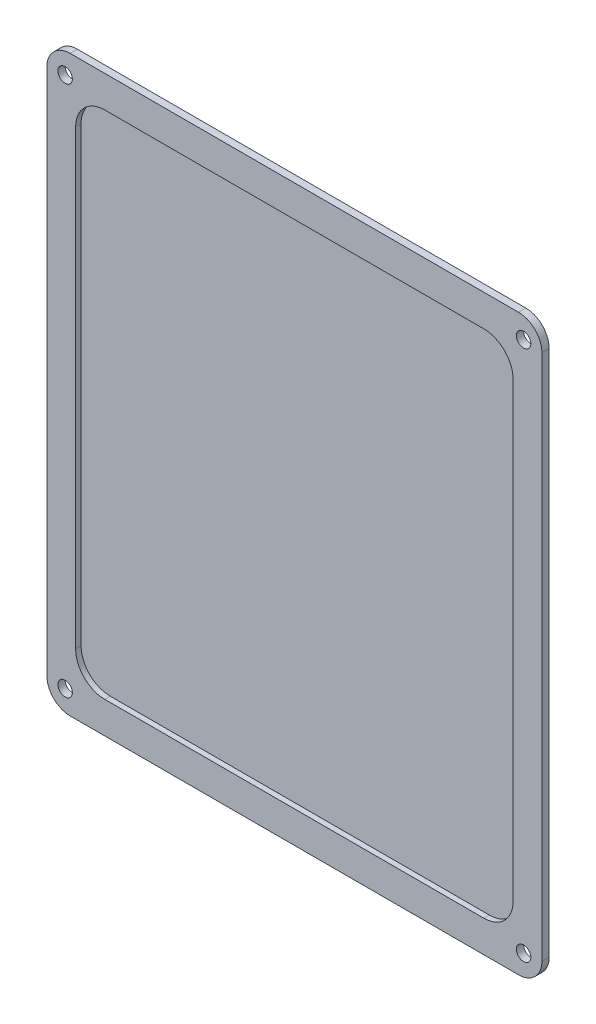
SolidWorks part; units mm, degrees
material "ABS"
ref_plane "Front Plane" through (0, 0, 0) normal (0, 0, 1) x (1, 0, 0)
ref_plane "Top Plane" through (0, 0, 0) normal (0, 1, 0) x (1, 0, 0)
ref_plane "Right Plane" through (0, 0, 0) normal (1, 0, 0) x (0, 0, -1)
sketch "Sketch1" plane through (0, 0, 0) normal (0, 0, 1) x (1, 0, 0)
  line L0 (-49.911, 57.8485) -> (-53.8932, 62.464) construction
  line L1 (-49.911, -57.8485) -> (49.911, -57.8485) construction
  line L2 (-49.911, -57.8485) -> (-49.911, 57.8485) construction
  line L3 (-49.911, 57.8485) -> (49.911, 57.8485) construction
  line L4 (49.911, -57.8485) -> (49.911, 57.8485) construction
  line L5 (-49.911, -57.8485) -> (49.911, 57.8485) construction
  line L6 (-49.911, 57.8485) -> (49.911, -57.8485) construction
  line L8 (53.8932, -62.464) -> (-53.8932, -62.464)
  line L9 (53.8932, -62.464) -> (53.8932, 62.464)
  line L10 (53.8932, 62.464) -> (-53.8932, 62.464)
  line L11 (-53.8932, -62.464) -> (-53.8932, 62.464)
  line L12 (53.8932, -62.464) -> (-53.8932, 62.464) construction
  line L13 (53.8932, 62.464) -> (-53.8932, -62.464) construction
  circle A0 centre (-49.911, 57.8485) radius 1.5748
  circle A1 centre (49.911, 57.8485) radius 1.5748
  circle A2 centre (49.911, -57.8485) radius 1.5748
  circle A3 centre (-49.911, -57.8485) radius 1.5748
  point P0 (0, 0)
  point P10 (0, 0)
  dimension "D3" = 3.1496
  dimension "D1" = 115.697
  dimension "D2" = 99.822
  dimension "D4" = 6.096
extrude "Boss-Extrude1" add sketch "Sketch1" along normal blind 1.5875
fillet "Fillet1" radius 5.08 4 edges at (-53.8932, -62.464, 0.7937) (53.8932, -62.464, 0.7937) (53.8932, 62.464, 0.7937) (-53.8932, 62.464, 0.7937)
sketch "Sketch4" plane through (0, 0, 1.5875) normal (0, 0, 1) x (1, 0, 0)
  line L1 (41.275, 55.5625) -> (-41.275, 55.5625)
  line L2 (47.625, 49.2125) -> (47.625, -49.2125)
  line L3 (41.275, -55.5625) -> (-41.275, -55.5625)
  line L4 (-47.625, 49.2125) -> (-47.625, -49.2125)
  line L5 (47.625, 55.5625) -> (-47.625, -55.5625) construction
  line L6 (47.625, -55.5625) -> (-47.625, 55.5625) construction
  arc A0 (47.625, 49.2125) -> (41.275, 55.5625) centre (41.275, 49.2125) ccw
  arc A1 (-41.275, 55.5625) -> (-47.625, 49.2125) centre (-41.275, 49.2125) ccw
  arc A2 (-47.625, -49.2125) -> (-41.275, -55.5625) centre (-41.275, -49.2125) ccw
  arc A3 (41.275, -55.5625) -> (47.625, -49.2125) centre (41.275, -49.2125) ccw
  point P0 (0, 0)
  dimension "D3" = 6.35
  dimension "D1" = 95.25
  dimension "D2" = 111.125
extrude "Cut-Extrude1" cut sketch "Sketch4" against normal through all
sketch "Sketch6" plane through (0, 0, 0) normal (0, 0, -1) x (-1, 0, 0)
  line L0 (-41.275, 55.5625) -> (41.275, 55.5625) construction
  line L1 (-47.625, -55.5625) -> (47.625, -55.5625)
  line L2 (-47.625, -55.5625) -> (-47.625, 55.5625)
  line L3 (-47.625, 55.5625) -> (47.625, 55.5625)
  line L4 (47.625, -55.5625) -> (47.625, 55.5625)
  line L5 (-47.625, -55.5625) -> (47.625, 55.5625) construction
  line L6 (-47.625, 55.5625) -> (47.625, -55.5625) construction
  line L7 (-47.625, -49.2125) -> (-47.625, 49.2125) construction
  point P0 (0, 0)
extrude "Boss-Extrude2" add sketch "Sketch6" against normal blind 0.3969
sketch "Sketch7" plane through (0, 0, 0) normal (0, 0, -1) x (-1, 0, 0)
  line L0 (-41.275, 55.5625) -> (41.275, 55.5625) construction
  line L1 (41.275, -55.5625) -> (-41.275, -55.5625)
  line L2 (47.625, -49.2125) -> (47.625, 49.2125)
  line L3 (41.275, 55.5625) -> (-41.275, 55.5625)
  line L4 (-47.625, -49.2125) -> (-47.625, 49.2125)
  line L5 (47.625, -55.5625) -> (-47.625, 55.5625) construction
  line L6 (47.625, 55.5625) -> (-47.625, -55.5625) construction
  line L7 (-47.625, -49.2125) -> (-47.625, 49.2125) construction
  arc A0 (-41.275, 55.5625) -> (-47.625, 49.2125) centre (-41.275, 49.2125) ccw
  arc A1 (-41.275, -55.5625) -> (-47.625, -49.2125) centre (-41.275, -49.2125) cw
  arc A2 (41.275, -55.5625) -> (47.625, -49.2125) centre (41.275, -49.2125) ccw
  arc A3 (47.625, 49.2125) -> (41.275, 55.5625) centre (41.275, 49.2125) ccw
  point P0 (0, 0)
  dimension "D1" = 6.35
split line "Split Line1"
